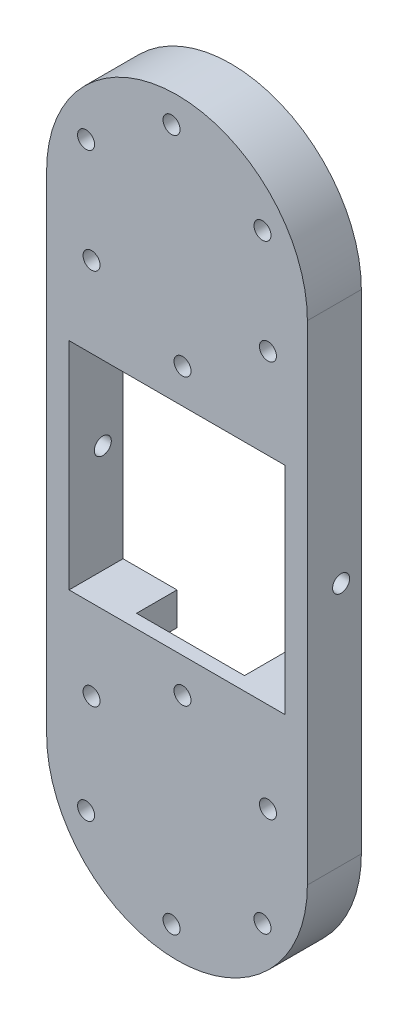
SolidWorks part; units mm, degrees
material "6061-T6 (SS)"
ref_plane "Front Plane" through (0, 0, 0) normal (0, 0, 1) x (1, 0, 0)
ref_plane "Top Plane" through (0, 0, 0) normal (0, 1, 0) x (1, 0, 0)
ref_plane "Right Plane" through (0, 0, 0) normal (1, 0, 0) x (0, 0, -1)
sketch "Sketch1" plane through (0, 0, 0) normal (0, 0, 1) x (1, 0, 0)
  line L2 (0, 57.5) -> (0, -57.5) construction
  line L3 (-30.675, 0) -> (30.675, 0) construction
  line L4 (0, -25.4) -> (0, -88.175) construction
  line L5 (25.4, -25.4) -> (-25.4, -25.4)
  line L6 (25.4, -25.4) -> (25.4, 25.4)
  line L7 (25.4, 25.4) -> (-25.4, 25.4)
  line L8 (-25.4, -25.4) -> (-25.4, 25.4)
  line L9 (25.4, -25.4) -> (-25.4, 25.4) construction
  line L10 (25.4, 25.4) -> (-25.4, -25.4) construction
  line L11 (30.675, 57.5) -> (30.675, -57.5)
  line L13 (-30.675, -57.5) -> (-30.675, 57.5)
  circle A2 centre (0, -57.5) radius 27.5
  circle A3 centre (0, 57.5) radius 27.5
  arc A6 (30.675, 57.5) -> (-30.675, 57.5) centre (0, 57.5) ccw
  arc A7 (30.675, -57.5) -> (-30.675, -57.5) centre (0, -57.5) cw
  point P8 (0, 0)
  point P18 (0, 0)
  dimension "D2" = 61.35
  dimension "D4" = 55
  dimension "D5" = 30.675
  dimension "D1" = 115
  dimension "D6" = 50.8
  dimension "D7" = 50.8
extrude "Boss-Extrude1" add sketch "Sketch1" along normal blind 12.7
sketch "Sketch2" plane through (0, 0, 12.7) normal (0, 0, 1) x (1, 0, 0)
  line L0 (-30.675, 0) -> (30.675, 0) construction
  line L7 (-27.5, 57.5) -> (27.5, 57.5) construction
  line L15 (-25.4, -25.4) -> (25.4, -25.4) construction
  line L16 (25.4, -25.4) -> (-25.4, -25.4)
  line L17 (25.4, -25.4) -> (25.4, 25.4)
  line L18 (25.4, 25.4) -> (-25.4, 25.4)
  line L19 (-25.4, -25.4) -> (-25.4, 25.4)
  line L20 (25.4, -25.4) -> (-25.4, 25.4) construction
  line L21 (25.4, 25.4) -> (-25.4, -25.4) construction
  line L22 (-30.675, -57.5) -> (30.675, -57.5) construction
  line L23 (30.675, -57.5) -> (30.675, 57.5)
  line L24 (-30.675, 57.5) -> (-30.675, -57.5)
  line L25 (30.675, -57.5) -> (30.675, 57.5)
  line L26 (-30.675, 57.5) -> (-30.675, -57.5)
  line L27 (25.4, -25.4) -> (25.4, 25.4) construction
  circle A2 centre (0, 57.5) radius 27.5 construction
  circle A6 centre (0, 57.5) radius 24 construction
  circle A7 centre (-1.2907, 81.4653) radius 2
  circle A8 centre (20.1092, 70.6004) radius 2
  circle A9 centre (21.3999, 46.6352) radius 2
  circle A10 centre (1.2907, 33.5347) radius 2
  circle A11 centre (-20.1092, 44.3996) radius 2
  circle A12 centre (-21.3999, 68.3648) radius 2
  circle A13 centre (0, -57.5) radius 24 construction
  circle A14 centre (-21.3999, -68.3648) radius 2
  circle A15 centre (-20.1092, -44.3996) radius 2
  circle A16 centre (1.2907, -33.5347) radius 2
  circle A17 centre (21.3999, -46.6352) radius 2
  circle A18 centre (20.1092, -70.6004) radius 2
  circle A19 centre (-1.2907, -81.4653) radius 2
  arc A25 (-30.675, -57.5) -> (30.675, -57.5) centre (0, -57.5) ccw
  arc A26 (30.675, 57.5) -> (-30.675, 57.5) centre (0, 57.5) ccw
  arc A27 (-30.675, -57.5) -> (30.675, -57.5) centre (0, -57.5) ccw
  arc A28 (30.675, 57.5) -> (-30.675, 57.5) centre (0, 57.5) ccw
  point P25 (0, 57.5)
  point P37 (0, -57.5)
  point P38 (0, 0)
  dimension "D3" = 48
  dimension "D4" = 4
  dimension "D1" = 0
  dimension "D5" = 6
extrude "Boss-Extrude2" add sketch "Sketch2" against normal blind 3.175
sketch "Sketch7" plane through (-30.675, 0, 0) normal (-1, 0, 0) x (0, 0, 1)
  line L0 (4.7625, 10.2) -> (4.7625, -10.2) construction
  circle A0 centre (4.7625, 0) radius 2
  dimension "D1" = 4
extrude "Cut-Extrude4" cut sketch "Sketch7" against normal blind 10
mirror "Mirror2" about plane through (0, 0, 0) normal (1, 0, 0) of "Cut-Extrude4"
sketch "Sketch8" plane through (0, 0, 0) normal (0, 0, -1) x (-1, 0, 0)
  line L5 (-12.7, -37.5) -> (12.7, -37.5)
  line L6 (-12.7, -37.5) -> (-12.7, 37.5)
  line L7 (-12.7, 37.5) -> (12.7, 37.5)
  line L8 (12.7, -37.5) -> (12.7, 37.5)
  line L9 (-12.7, -37.5) -> (12.7, 37.5) construction
  line L10 (-12.7, 37.5) -> (12.7, -37.5) construction
  point P0 (0, 0)
  dimension "D1" = 75
  dimension "D2" = 25.4
extrude "Cut-Extrude5" cut sketch "Sketch8" against normal up to surface (9.525 mm away) up to face at (27.5, 57.5, 9.525)
equation "\"d\"=5"
